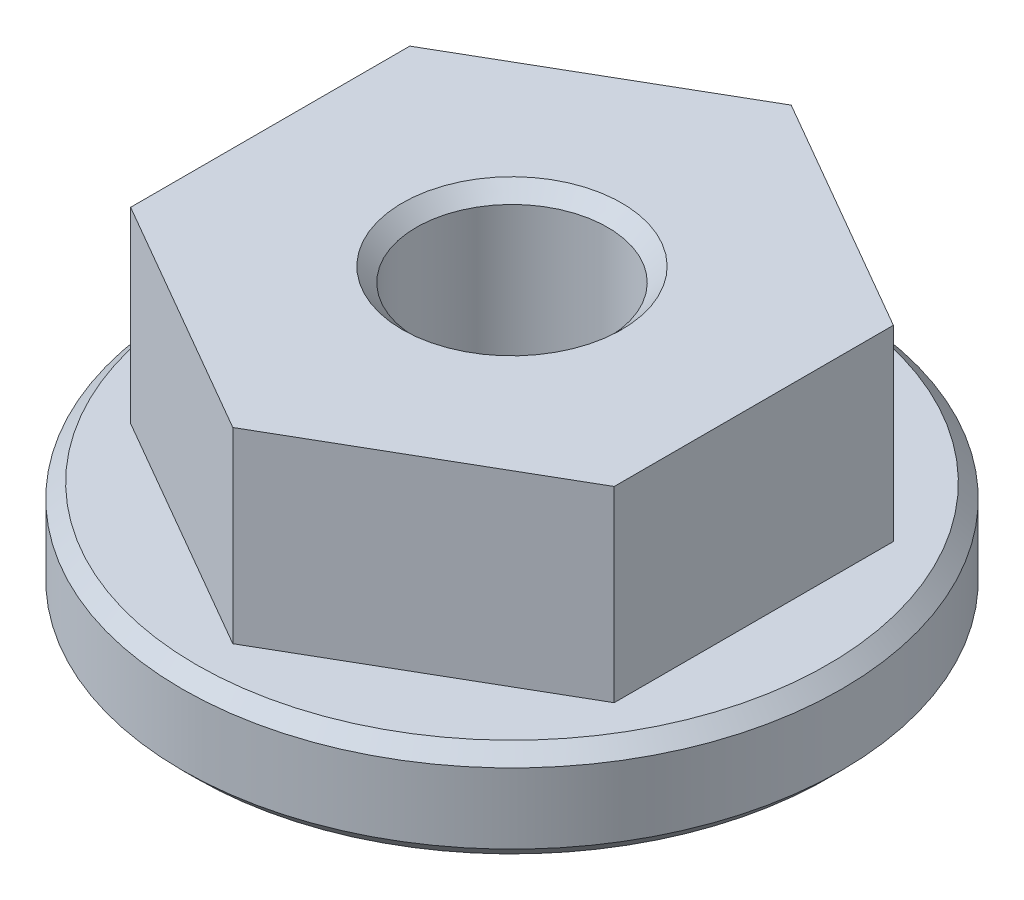
SolidWorks part; units mm, degrees
ref_plane "Front Plane" through (0, 0, 0) normal (0, 0, 1) x (1, 0, 0)
ref_plane "Top Plane" through (0, 0, 0) normal (0, 1, 0) x (1, 0, 0)
ref_plane "Right Plane" through (0, 0, 0) normal (1, 0, 0) x (0, 0, -1)
sketch "Sketch1" plane through (0, 0, 0) normal (0, 1, 0) x (1, 0, 0)
  circle A0 centre (0, 0) radius 5.9531
  dimension "D1" = 11.9062
extrude "Boss-Extrude1" add sketch "Sketch1" along normal blind 1.778
sketch "Sketch2" plane through (0, 1.778, 0) normal (0, 1, 0) x (1, 0, 0)
  line L1 (4.3656, -2.5205) -> (4.3656, 2.5205)
  line L2 (4.3656, 2.5205) -> (0, 5.041)
  line L3 (0, 5.041) -> (-4.3656, 2.5205)
  line L4 (-4.3656, 2.5205) -> (-4.3656, -2.5205)
  line L5 (-4.3656, -2.5205) -> (0, -5.041)
  line L6 (0, -5.041) -> (4.3656, -2.5205)
  circle A0 centre (0, 0) radius 4.3656 construction
  circle A1 centre (0, 0) radius 5.9531 construction
  dimension "D1" = 8.7312
extrude "Boss-Extrude2" add sketch "Sketch2" along normal blind 3.3814
hole_wizard "#8-32 Tapped Hole1" positions "Sketch3" profile "Sketch4" tap size "#8-32" standard "ANSI Inch" end condition through all
sketch "Sketch3" plane through (0, 5.1594, 0) normal (0, 1, 0) x (1, 0, 0)
  point P0 (0, 0)
sketch "Sketch4" plane through (0, 5.1594, 0) normal (1, 0, 0) x (0, 0, 1)
  line L0 (0, 0) -> (0, 5.1594)
  line L1 (0, 5.1594) -> (1.7272, 5.1594)
  line L2 (1.7272, 5.1594) -> (1.7272, 0)
  line L5 (1.7272, 0) -> (0, 0)
  line L11 (0, -6.35) -> (0, 107.95) construction
  dimension "Thru Tap Drill Dia." = 3.4544
  dimension "Thru Tap Drill Depth" = 5.1594
cosmetic thread "Hole Thread1" parameters "D2"=4.1656
chamfer "Chamfer1" distance 0.254 angle 45 4 edges at (0, 0, 1.7272) (0, 5.1594, 1.7272) (0, 1.778, 5.9531) (0, 0, 5.9531)
